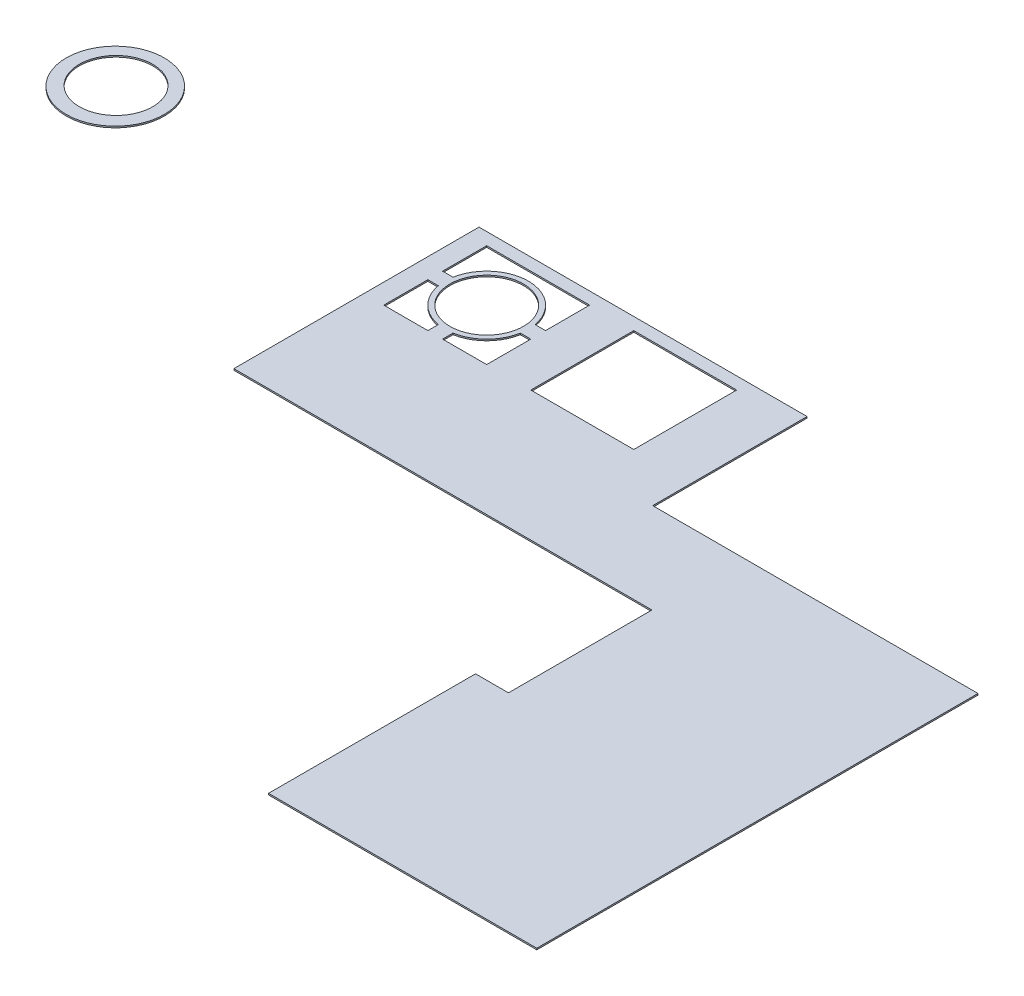
SolidWorks part; units mm, degrees
ref_plane "Front Plane" through (0, 0, 0) normal (0, 0, 1) x (1, 0, 0)
ref_plane "Top Plane" through (0, 0, 0) normal (0, 1, 0) x (1, 0, 0)
ref_plane "Right Plane" through (0, 0, 0) normal (1, 0, 0) x (0, 0, -1)
sketch "Sketch1" plane through (0, 0, 0) normal (0, 1, 0) x (1, 0, 0)
  line L0 (0, 0) -> (0, 5)
  line L1 (0, 5) -> (6.692, 5)
  line L2 (6.692, 5) -> (6.692, 1.851)
  line L3 (6.692, 1.851) -> (13.328, 1.851)
  line L4 (13.328, 1.851) -> (13.328, -7.149)
  line L5 (13.328, -7.149) -> (7.856, -7.149)
  line L6 (7.856, -7.149) -> (7.856, -2.927)
  line L7 (7.856, -2.927) -> (8.528, -2.927)
  line L8 (8.528, -2.927) -> (8.528, 0)
  line L9 (8.528, 0) -> (0, 0)
  line L11 (0.407, 4.75) -> (2.507, 4.75)
  line L12 (0.407, 4.75) -> (0.407, 2.65)
  line L13 (0.407, 2.65) -> (2.507, 2.65)
  line L14 (2.507, 4.75) -> (2.507, 2.65)
  line L15 (3.407, 4.75) -> (5.507, 4.75)
  line L16 (3.407, 4.75) -> (3.407, 2.65)
  line L17 (3.407, 2.65) -> (5.507, 2.65)
  line L18 (5.507, 4.75) -> (5.507, 2.65)
  dimension "D1" = 5
  dimension "D2" = 6.692
  dimension "D3" = 9
  dimension "D4" = 5.472
  dimension "D5" = 8.528
  dimension "D6" = 2.927
  dimension "D7" = 0.672
  dimension "D8" = 4.222
  dimension "D9" = 2.1
  dimension "D10" = 2.1
  dimension "D11" = 2.1
  dimension "D12" = 2.1
  dimension "D13" = 0.407
  dimension "D14" = 0.25
  dimension "D15" = 0.25
  dimension "D16" = 0.9
extrude "Boss-Extrude1" add sketch "Sketch1" along normal blind 0.03
sketch "Sketch2" plane through (0, 0.03, 0) normal (0, 1, 0) x (1, 0, 0)
  line L0 (2.507, 2.65) -> (2.507, 4.75) construction
  line L1 (2.507, 3.55) -> (2.2937, 3.55)
  line L2 (2.507, 3.55) -> (2.507, 3.85)
  line L3 (2.507, 3.85) -> (2.2937, 3.85)
  line L5 (0.407, 2.65) -> (2.507, 2.65) construction
  line L6 (1.307, 2.65) -> (1.607, 2.65)
  line L7 (1.307, 2.65) -> (1.307, 2.8633)
  line L9 (1.607, 2.65) -> (1.607, 2.8633)
  line L10 (0.407, 4.75) -> (0.407, 2.65) construction
  line L11 (0.407, 3.55) -> (0.6203, 3.55)
  line L12 (0.407, 3.55) -> (0.407, 3.85)
  line L13 (0.407, 3.85) -> (0.6203, 3.85)
  arc A0 (1.607, 2.8633) -> (2.2937, 3.55) centre (1.457, 3.7) ccw
  arc A1 (2.2937, 3.85) -> (0.6203, 3.85) centre (1.457, 3.7) ccw
  arc A2 (0.6203, 3.55) -> (1.307, 2.8633) centre (1.457, 3.7) ccw
  point P20 (1.457, 2.65)
  point P21 (1.457, 2.65)
  point P22 (2.507, 3.7)
  point P23 (2.507, 3.7)
  point P24 (0.407, 3.7)
  point P25 (0.407, 3.7)
  dimension "D1" = 1.7
  dimension "D9" = 0
  dimension "D2" = 0.3
  dimension "D3" = 0.3
  dimension "D4" = 0.3
  dimension "D5" = 0
  dimension "D6" = 0
  dimension "D7" = 0
  dimension "D8" = 0
extrude "Boss-Extrude2" add sketch "Sketch2" against normal up to surface (0.03 mm away) up to face at (7.2808, 0, 0.645)
sketch "Sketch3" plane through (0, 0.03, 0) normal (0, 1, 0) x (1, 0, 0)
  line L1 (6.692, 5) -> (0, 5) construction
  line L2 (0, 5) -> (0, 0) construction
  circle A0 centre (-6.2, 3.78) radius 1
  dimension "D1" = 2
  dimension "D2" = 6.2
  dimension "D3" = 1.22
extrude "Boss-Extrude3" add sketch "Sketch3" against normal blind 0.03 separate body
sketch "Sketch4" plane through (0, 0.03, 0) normal (0, 1, 0) x (1, 0, 0)
  circle A0 centre (-6.204, 3.8) radius 0.75
  circle A1 centre (1.457, 3.7) radius 0.75
extrude "Cut-Extrude1" cut sketch "Sketch4" against normal through all both
